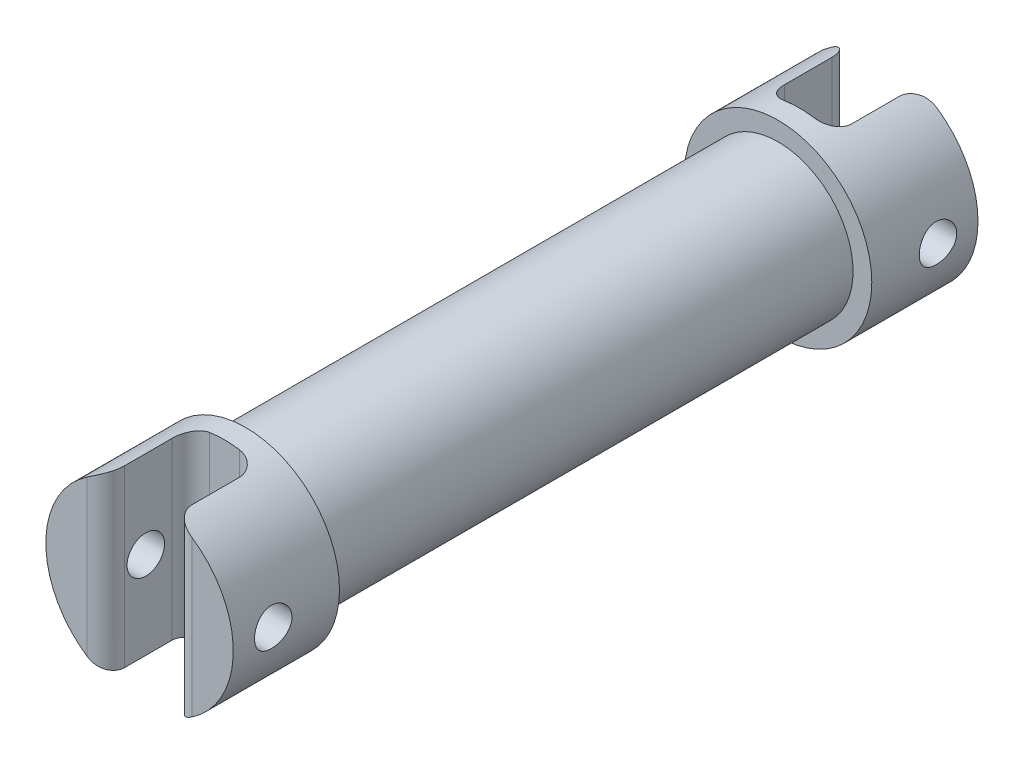
SolidWorks part; units mm, degrees
ref_plane "Front Plane" through (0, 0, 0) normal (0, 0, 1) x (1, 0, 0)
ref_plane "Top Plane" through (0, 0, 0) normal (0, 1, 0) x (1, 0, 0)
ref_plane "Right Plane" through (0, 0, 0) normal (1, 0, 0) x (0, 0, -1)
sketch "Sketch1" plane through (0, 0, 0) normal (0, 0, 1) x (1, 0, 0)
  circle A0 centre (0, 0) radius 7.5
  dimension "D1" = 15
extrude "Boss-Extrude1" add sketch "Sketch1" along normal blind 8.5
sketch "Sketch2" plane through (0, 0, 8.5) normal (0, 0, 1) x (1, 0, 0)
  line L0 (0, 0) -> (2.7, 0) construction
  line L1 (0, 0) -> (-2.7, 0) construction
  line L2 (2.7, 0) -> (2.7, 13.7828)
  line L3 (-2.7, 0) -> (-2.7, 13.7828)
  line L4 (-2.7, 13.7828) -> (2.7, 13.7828)
  line L5 (2.7, 0) -> (2.7, -14.1285)
  line L6 (2.7, -14.1285) -> (-2.7, -14.1285)
  line L7 (-2.7, -14.1285) -> (-2.7, 0)
  dimension "D1" = 2.7
  dimension "D2" = 2.7
extrude "Cut-Extrude1" cut sketch "Sketch2" against normal blind 6.8
sketch "Sketch3" plane through (-2.7, 0, 0) normal (1, 0, 0) x (0, 0, -1)
  line L0 (-8.5, 0) -> (-5.3, 0) construction
  line L1 (-8.5, 6.9971) -> (-8.5, -6.9971) construction
  circle A0 centre (-5.3, 0) radius 1.5
  dimension "D1" = 3.2
extrude "Cut-Extrude2" cut sketch "Sketch3" along normal through all and the other way through all
fillet "Fillet1" radius 1.5 4 edges at (2.7, 0, 8.5) (2.7, 0, 1.7) (-2.7, 0, 1.7) (-2.7, 0, 8.5)
ref_plane "Plane1" through (0, 0, -21.3) normal (0, 0, -1) x (-1, 0, 0)
sketch "Sketch5" plane through (0, 0, -21.3) normal (0, 0, -1) x (-1, 0, 0)
  circle A0 centre (0, 0) radius 6
  dimension "D1" = 12
extrude "Boss-Extrude3" add sketch "Sketch5" along normal blind 21.3 and the other way up to next
mirror "Mirror1" about plane through (0, 0, -21.3) normal (0, 0, -1) of "Fillet1", "Cut-Extrude2", "Cut-Extrude1", "Boss-Extrude1"
